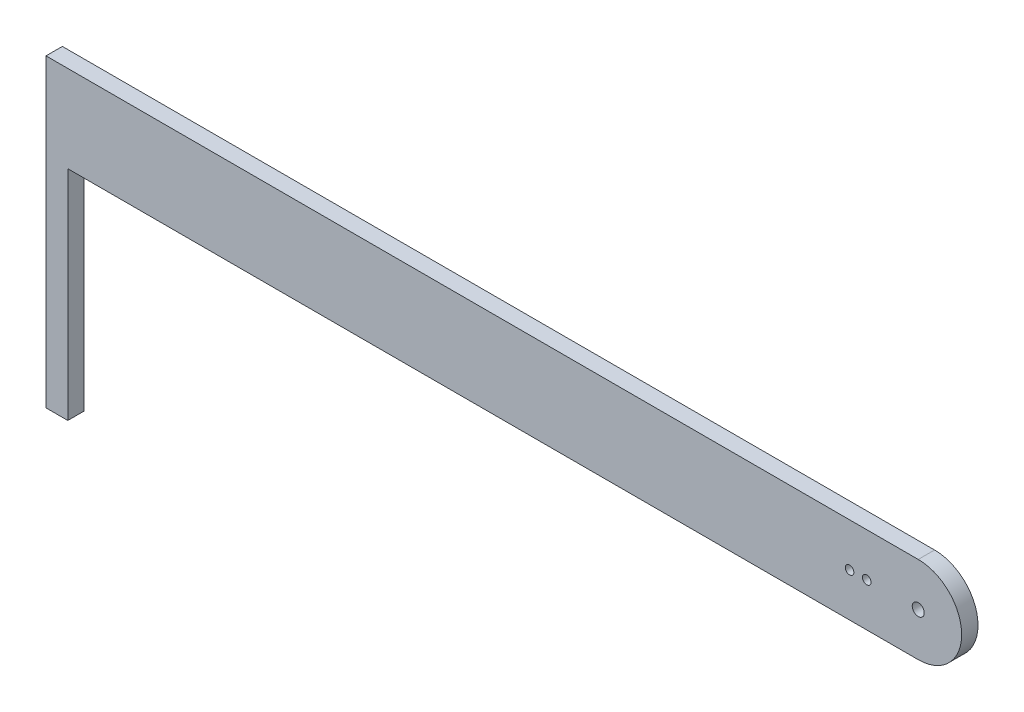
SolidWorks part; units mm, degrees
ref_plane "Front Plane" through (0, 0, 0) normal (0, 0, 1) x (1, 0, 0)
ref_plane "Top Plane" through (0, 0, 0) normal (0, 1, 0) x (1, 0, 0)
ref_plane "Right Plane" through (0, 0, 0) normal (1, 0, 0) x (0, 0, -1)
sketch "Sketch1" plane through (0, 0, 0) normal (0, 0, 1) x (1, 0, 0)
  line L1 (0, 12.6426) -> (-254, 12.6426)
  line L2 (-247.65, -76.1426) -> (-254, -76.1426)
  line L3 (0, -12.6426) -> (-247.65, -12.6426)
  line L4 (-254, 12.6426) -> (-254, -12.6426)
  line L5 (-247.65, -76.1426) -> (-247.65, -12.6426)
  line L7 (-254, -76.1426) -> (-254, -12.6426)
  arc A0 (0, -12.6426) -> (0, 12.6426) centre (0, 0) ccw
  dimension "D1" = 254
  dimension "D2" = 25.2852
  dimension "D3" = 6.35
  dimension "D4" = 63.5
extrude "Boss-Extrude1" add sketch "Sketch1" along normal blind 4.7625
sketch "Sketch3" plane through (0, 0, 4.7625) normal (0, 0, 1) x (1, 0, 0)
  circle A0 centre (-15, 0) radius 1.25
  circle A1 centre (-20, 0) radius 1.25
extrude "Cut-Extrude1" cut sketch "Sketch3" against normal through all
sketch "Sketch4" plane through (0, 0, 4.7625) normal (0, 0, 1) x (1, 0, 0)
  circle A0 centre (0, 0) radius 1.75
extrude "Cut-Extrude2" cut sketch "Sketch4" against normal through all
